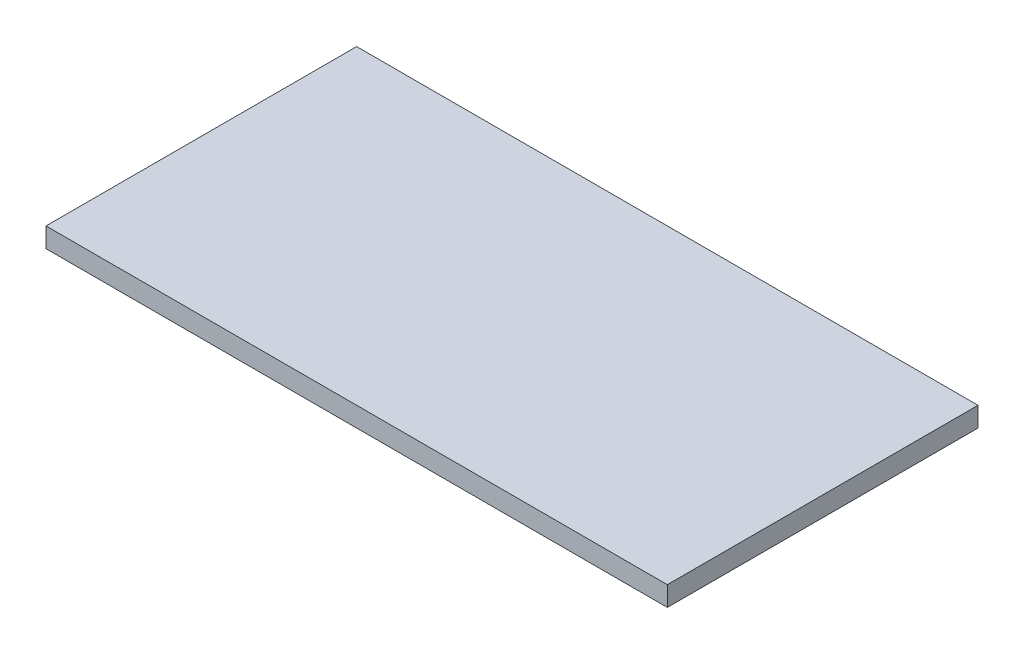
SolidWorks part; units mm, degrees
ref_plane "Front Plane" through (0, 0, 0) normal (0, 0, 1) x (1, 0, 0)
ref_plane "Top Plane" through (0, 0, 0) normal (0, 1, 0) x (1, 0, 0)
ref_plane "Right Plane" through (0, 0, 0) normal (1, 0, 0) x (0, 0, -1)
sketch "Sketch1" plane through (0, 0, 0) normal (0, 1, 0) x (1, 0, 0)
  line L1 (-50, -25) -> (50, -25)
  line L2 (-50, -25) -> (-50, 25)
  line L3 (-50, 25) -> (50, 25)
  line L4 (50, -25) -> (50, 25)
  line L5 (-50, -25) -> (50, 25) construction
  line L6 (-50, 25) -> (50, -25) construction
  point P0 (0, 0)
  dimension "D1" = 100
  dimension "D2" = 50
extrude "Boss-Extrude1" add sketch "Sketch1" along normal blind 3.175
